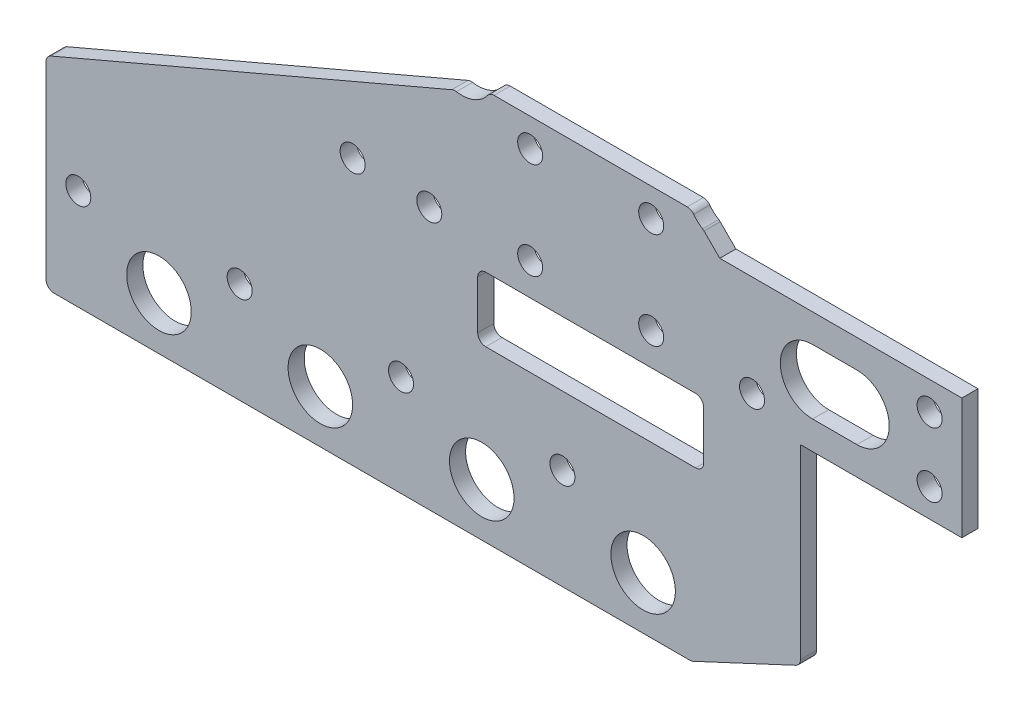
SolidWorks part; units mm, degrees
material "Thornel Mat VMA"
ref_plane "前视基准面" through (0, 0, 0) normal (0, 0, 1) x (1, 0, 0)
ref_plane "上视基准面" through (0, 0, 0) normal (0, 1, 0) x (1, 0, 0)
ref_plane "右视基准面" through (0, 0, 0) normal (1, 0, 0) x (0, 0, -1)
sketch "草图1" plane through (0, 0, 0) normal (0, 0, 1) x (1, 0, 0)
  line L0 (0, 0) -> (-80, 0)
  line L3 (0, 48.5) -> (-25, 48.5)
  line L5 (-80, 25) -> (-80, 0)
  line L6 (-80, 12.5) -> (0, 12.5) construction
  line L7 (-12.5, 0) -> (-12.5, 98.5061) construction
  line L65 (0, 48.5) -> (3.5, 45)
  line L71 (0, 0) -> (-25, 25) construction
  line L80 (-25, 73.2333) -> (-25, 25) construction
  line L82 (-25, 25) -> (-80, 25) construction
  line L83 (-25, 25) -> (0, 25) construction
  line L85 (1.5, 21) -> (-26.5, 21)
  line L86 (1.5, 21) -> (1.5, 29)
  line L87 (1.5, 29) -> (-26.5, 29)
  line L88 (-26.5, 21) -> (-26.5, 29)
  line L89 (1.5, 21) -> (-26.5, 29) construction
  line L90 (1.5, 29) -> (-26.5, 21) construction
  line L92 (13.5, 6.2952) -> (0, 0)
  line L93 (1.5, 25) -> (10.53, 25) construction
  line L94 (0, 12.5) -> (0, 0) construction
  line L95 (-25, 48.5) -> (-35.6716, 43.9403)
  line L101 (13.5, 33) -> (13.5, 34.7361) construction
  line L104 (-48, 44.5) -> (-25, 44.5) construction
  line L113 (-48, 44.5) -> (-48, 64.5) construction
  line L116 (-25, 48.5) -> (-25, 44.5) construction
  line L117 (0.5, 48) -> (33.5, 48) construction
  line L126 (-48, 64.5) -> (-25, 64.5) construction
  line L128 (-48, 44.5) -> (-80, 25) construction
  line L129 (33.5, 48) -> (33.5, 33) construction
  line L130 (33.5, 33) -> (26.7216, 33) construction
  line L134 (21.5, 33) -> (13.5, 33) construction
  line L135 (15, 37.5) -> (20.5, 37.5) construction
  line L136 (15, 41.5) -> (20.5, 41.5)
  line L137 (15, 33.5) -> (20.5, 33.5)
  line L141 (-35.6716, 43.9403) -> (-80, 25)
  line L169 (33.5, 45) -> (3.5, 45)
  line L172 (13.5, 30) -> (13.5, 6.2952)
  line L173 (33.5, 45) -> (33.5, 30)
  line L174 (33.5, 30) -> (13.5, 30)
  circle A1 centre (-36, 12.5) radius 1.55
  circle A2 centre (-96, 12.5) radius 1.55 construction
  circle A3 centre (-56, 12.5) radius 1.55
  circle A4 centre (-76, 12.5) radius 1.55
  circle A28 centre (-42, 33) radius 1.55
  circle A35 centre (-16, 12.5) radius 1.55
  circle A36 centre (-20, 45) radius 1.55
  circle A37 centre (-20, 33) radius 1.55
  circle A38 centre (-5, 45) radius 1.55
  circle A39 centre (-5, 33) radius 1.55
  circle A40 centre (29.5, 45) radius 1.55 construction
  circle A41 centre (29.5, 37) radius 1.55 construction
  circle A42 centre (-32.5, 32.5) radius 1.55
  circle A43 centre (7.5, 32.5) radius 1.55
  circle A44 centre (-86, 6.5) radius 4 construction
  circle A45 centre (-66, 6.5) radius 4
  circle A46 centre (-46, 6.5) radius 4
  circle A47 centre (-26, 6.5) radius 4
  circle A48 centre (-6, 6.5) radius 4
  arc A49 (15, 41.5) -> (15, 33.5) centre (15, 37.5) ccw
  arc A50 (20.5, 33.5) -> (20.5, 41.5) centre (20.5, 37.5) ccw
  circle A53 centre (29.5, 41.5) radius 1.55
  circle A54 centre (29.5, 33.5) radius 1.55
  point P22 (-12.5, 12.5)
  point P31 (-12.5, 25)
  point P70 (17.75, 37.5)
  dimension "D6" = 3.1
  dimension "D14" = 20
  dimension "D8" = 20
  dimension "D13" = 3.1
  dimension "D23" = 8
  dimension "D32" = 4
  dimension "D33" = 4
  dimension "D34" = 8
  dimension "D42" = 33.5
  dimension "D18" = 3.1
  dimension "D22" = 3.1
  dimension "D51" = 3.1
  dimension "D52" = 3.5
  dimension "D1" = 48.5
  dimension "D3" = 80
  dimension "D4" = 25
  dimension "D5" = 25
  dimension "D7" = 7
  dimension "D9" = 20
  dimension "D10" = 20
  dimension "D11" = 45
  dimension "D12" = 8
  dimension "D15" = 12
  dimension "D16" = 15
  dimension "D17" = 7.5
  dimension "D19" = 65
  dimension "D20" = 12
  dimension "D21" = 28
  dimension "D24" = 8
  dimension "D25" = 37
  dimension "D26" = 44.5
  dimension "D27" = 7.5
  dimension "D28" = 6.5
  dimension "D29" = 20
  dimension "D30" = 42
  dimension "D31" = 23
  dimension "D35" = 10
  dimension "D36" = 5
  dimension "D37" = 20
  dimension "D38" = 8
  dimension "D39" = 8
  dimension "D40" = 38
  dimension "D41" = 3.5
  dimension "D43" = 4
  dimension "D44" = 3
  dimension "D45" = 3.5
  dimension "D46" = 3.5
  dimension "D47" = 9
  dimension "D48" = 15
  dimension "D49" = 42
  dimension "D50" = 8
extrude "凸台-拉伸1" add sketch "草图1" along normal blind 2
sketch "草图2" plane through (0, 0, 2) normal (0, 0, 1) x (1, 0, 0)
  line L1 (-12.5, 48.5) -> (-12.5, 40.7347) construction
  line L2 (0, 48.5) -> (-25, 48.5) construction
  line L3 (0, 48.5) -> (-25, 48.5) construction
  circle A0 centre (3.4641, 50.5) radius 4
  circle A1 centre (-28.4641, 50.5) radius 4
  dimension "D1" = 8
  dimension "D2" = 2
extrude "切除-拉伸1" cut sketch "草图2" against normal blind 10
fillet "圆角2" radius 1 12 edges at (1.5, 21, 1) (1.5, 29, 1) (-26.5, 21, 1) (-26.5, 29, 1) (1.4641, 47.0359, 1) (0, 0, 1) (-80, 0, 1) (-80, 25, 1) (-25, 48.5, 1) (0, 48.5, 1) (-29.4134, 46.6143, 1) (13.5, 6.2952, 1)
sketch "草图3" plane through (0, 0, 0) normal (0, 0, -1) x (-1, 0, 0)
  line L0 (0.5359, 48.5) -> (24.4641, 48.5) construction
  line L1 (-6, 39.5) -> (-16, 39.5)
  line L2 (-6, 39.5) -> (-6, 49.5)
  line L3 (-6, 49.5) -> (-16, 49.5)
  line L4 (-16, 39.5) -> (-16, 49.5)
  line L5 (-6, 39.5) -> (-16, 49.5) construction
  line L6 (-6, 49.5) -> (-16, 39.5) construction
  circle A0 centre (5, 45) radius 1.55 construction
  point P0 (-11, 44.5)
  dimension "D1" = 9
  dimension "D2" = 11
  dimension "D3" = 10
sketch "草图4" plane through (0, 0, 0) normal (0, 0, -1) x (-1, 0, 0)
  line L0 (-3.5, 45) -> (-13.5, 35)
  line L1 (-13.5, 30) -> (-33.5, 30)
  line L2 (-33.5, 30) -> (-33.5, 45)
  line L3 (-33.5, 45) -> (-3.5, 45)
  line L4 (-1.5519, 46.9481) -> (-3.5, 45) construction
  line L5 (-13.5, 30) -> (-13.5, 35)
extrude "切除-拉伸2" [suppressed] cut sketch "草图4" against normal blind 10
